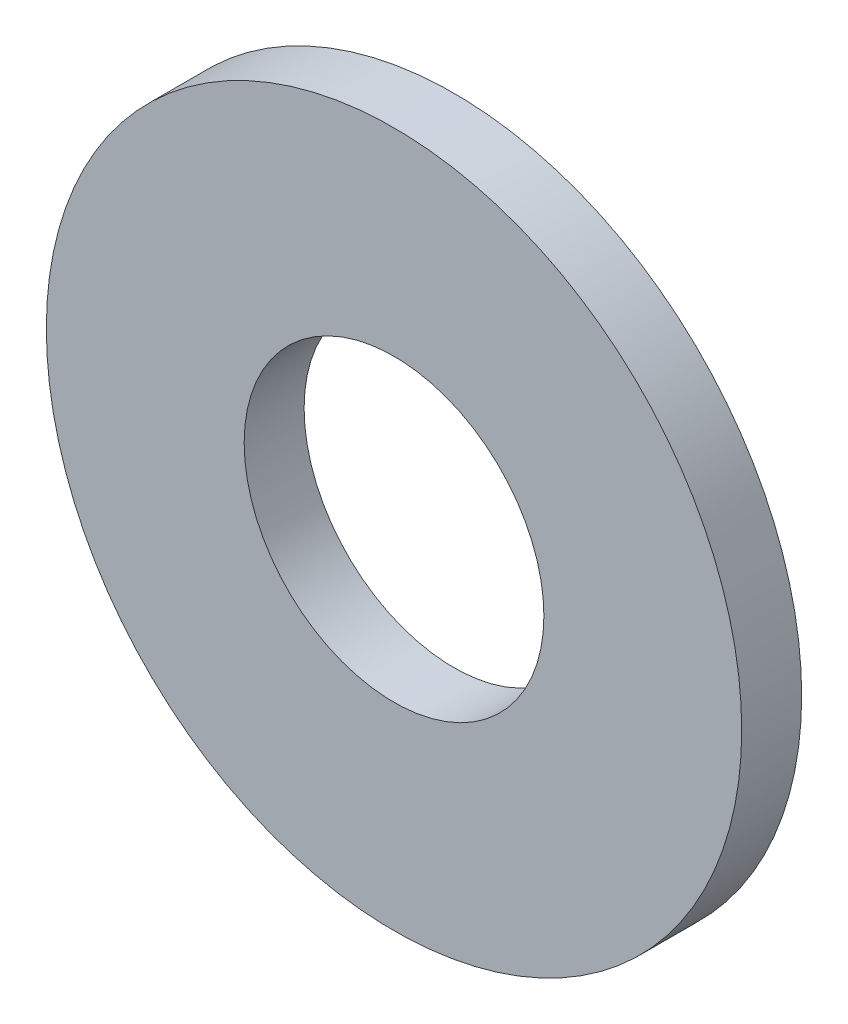
SolidWorks part; units mm, degrees
ref_plane "Plan de face" through (0, 0, 0) normal (0, 0, 1) x (1, 0, 0)
ref_plane "Plan de dessus" through (0, 0, 0) normal (0, 1, 0) x (1, 0, 0)
ref_plane "Plan de droite" through (0, 0, 0) normal (1, 0, 0) x (0, 0, -1)
sketch "Esquisse1" plane through (0, 0, 0) normal (0, 0, 1) x (1, 0, 0)
  circle A0 centre (0, 0) radius 2.5
  circle A1 centre (0, 0) radius 5.8
  dimension "D1" = 5
  dimension "D2" = 11.6
extrude "Boss.-Extru.1" add sketch "Esquisse1" along normal blind 1
